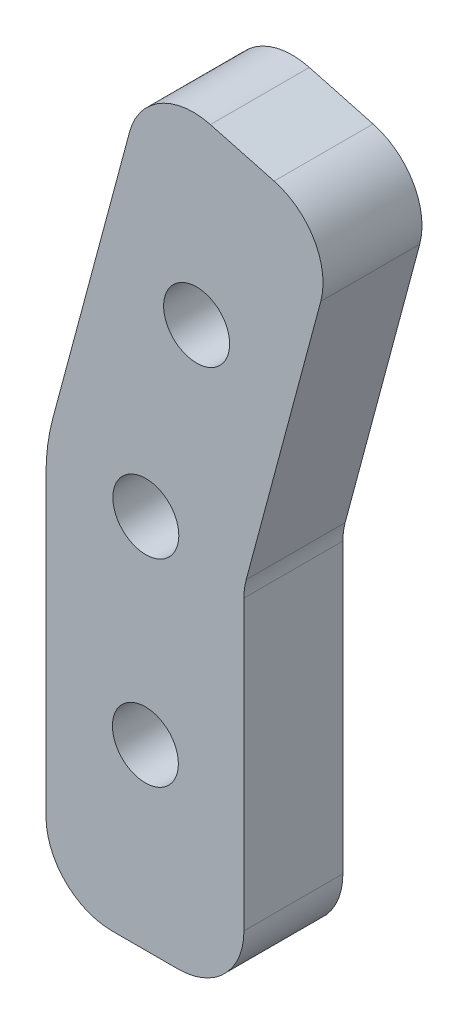
SolidWorks part; units mm, degrees
material "Delrin 2700 NC010, Low Viscosity Acetal Copolymer (SS)"
ref_plane "Front Plane" through (0, 0, 0) normal (0, 0, 1) x (1, 0, 0)
ref_plane "Top Plane" through (0, 0, 0) normal (0, 1, 0) x (1, 0, 0)
ref_plane "Right Plane" through (0, 0, 0) normal (1, 0, 0) x (0, 0, -1)
sketch "Sketch1" plane through (0, 0, 0) normal (0, 0, 1) x (1, 0, 0)
  line L1 (-9.525, -17.4625) -> (9.525, -17.4625)
  line L2 (-9.525, -17.4625) -> (-9.525, 17.4625)
  line L3 (-9.525, 17.4625) -> (9.525, 17.4625)
  line L4 (9.525, -17.4625) -> (9.525, 17.4625)
  line L5 (-9.525, -17.4625) -> (9.525, 17.4625) construction
  line L6 (-9.525, 17.4625) -> (9.525, -17.4625) construction
  point P0 (0, 0)
  dimension "D1" = 19.05
  dimension "D2" = 34.925
extrude "Boss-Extrude1" add sketch "Sketch1" along normal mid plane 9.525
sketch "Sketch2" plane through (0, 0, 4.7625) normal (0, 0, 1) x (1, 0, 0)
  line L0 (9.525, 17.4625) -> (18.5643, 51.1975)
  line L1 (18.5643, 51.1975) -> (0.1634, 56.128)
  line L2 (0.1634, 56.128) -> (-8.8759, 22.393)
  line L3 (-8.8759, 22.393) -> (9.525, 17.4625)
  line L4 (9.525, 17.4625) -> (-9.525, 17.4625) construction
  line L5 (9.525, -17.4625) -> (9.525, 17.4625) construction
  point P9 (-17.6404, 56.024)
  dimension "D1" = 34.925
  dimension "D2" = 165
extrude "Boss-Extrude2" add sketch "Sketch2" against normal up to surface (9.525 mm away) separate body up to face at (0, 0, -4.7625)
sketch "Sketch3" plane through (0, 0, 4.7625) normal (0, 0, 1) x (1, 0, 0)
  line L0 (-8.8759, 22.393) -> (9.525, 17.4625) construction
  line L1 (9.525, 17.4625) -> (-9.525, 17.4625) construction
  line L2 (-8.8759, 22.393) -> (9.525, 17.4625)
  line L3 (9.525, 17.4625) -> (-9.525, 17.4625)
  arc A0 (-8.8759, 22.393) -> (-9.525, 17.4625) centre (9.525, 17.4625) ccw
extrude "Boss-Extrude3" add sketch "Sketch3" against normal up to surface (9.525 mm away) up to face at (0, 0, -4.7625)
hole_wizard "1/4 (0.25) Diameter Hole1" positions "Sketch4" profile "Sketch5" hole size "1/4" standard "ANSI Inch" end condition through all
sketch "Sketch4" plane through (0, 0, 4.7625) normal (0, 0, 1) x (1, 0, 0)
  line L0 (9.525, 17.4625) -> (-9.362, 19.949) construction
  line L2 (0.0815, 18.7058) -> (9.3638, 53.6627) construction
  line L3 (18.5643, 51.1975) -> (0.1634, 56.128) construction
  line L5 (0, -17.4625) -> (0.0815, 18.7058) construction
  line L6 (-9.525, -17.4625) -> (9.525, -17.4625) construction
  arc A0 (-8.8759, 22.393) -> (-9.525, 17.4625) centre (9.525, 17.4625) ccw construction
  point P9 (0.0815, 18.7058)
  point P23 (4.9705, 37.1177)
  point P25 (0.0386, -0.3442)
  dimension "D1" = 19.05
  dimension "D2" = 19.05
sketch "Sketch5" plane through (0.0386, -0.3442, 4.7625) normal (1, 0, 0) x (0, -1, 0)
  line L0 (0, 0) -> (0, 9.525)
  line L1 (0, 9.525) -> (3.175, 9.525)
  line L2 (3.175, 9.525) -> (3.175, 0)
  line L5 (3.175, 0) -> (0, 0)
  line L11 (0, -6.35) -> (0, 107.95) construction
  dimension "Thru Hole Dia." = 6.35
  dimension "Thru Hole Depth" = 9.525
fillet "Fillet1" radius 6.35 5 edges at (9.525, 17.4625, 0) (0.1634, 56.128, 0) (-9.525, -17.4625, 0) (9.525, -17.4625, 0) (18.5643, 51.1975, 0)
equation "\"D2@Sketch4\"=\"D1@Sketch4\""
equation "\"D2@Sketch1\"=1.250in+.125"
equation "\"D1@Sketch2\"=1.250in+.125"
